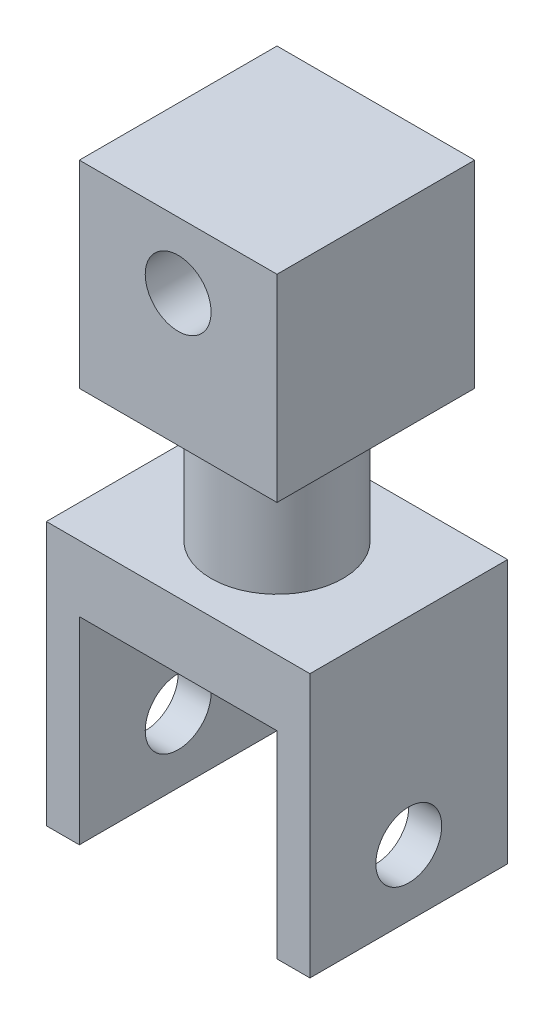
SolidWorks part; units mm, degrees
ref_plane "Front Plane" through (0, 0, 0) normal (0, 0, 1) x (1, 0, 0)
ref_plane "Top Plane" through (0, 0, 0) normal (0, 1, 0) x (1, 0, 0)
ref_plane "Right Plane" through (0, 0, 0) normal (1, 0, 0) x (0, 0, -1)
sketch "Sketch1" plane through (0, 0, 0) normal (0, 1, 0) x (1, 0, 0)
  line L0 (50.8, 76.2) -> (50.8, 0) construction
  line L6 (0, 0) -> (101.6, 0)
  line L7 (0, 0) -> (0, 76.2)
  line L8 (0, 76.2) -> (101.6, 76.2)
  line L9 (101.6, 0) -> (101.6, 76.2)
  line L10 (0, 0) -> (101.6, 76.2) construction
  line L11 (0, 76.2) -> (101.6, 0) construction
  point P7 (50.8, 38.1)
  dimension "D3" = 101.6
  dimension "D4" = 76.2
extrude "Boss-Extrude1" add sketch "Sketch1" along normal blind 101.6
sketch "Sketch3" plane through (0, 0, 0) normal (0, -1, 0) x (1, 0, 0)
  line L0 (101.6, -38.1) -> (0, -38.1) construction
  line L1 (101.6, 0) -> (101.6, -76.2) construction
  line L2 (0, 0) -> (0, -76.2) construction
  line L3 (0, -76.2) -> (101.6, -76.2) construction
  line L4 (88.9, 0) -> (12.7, 0)
  line L5 (88.9, 0) -> (88.9, -76.2)
  line L6 (88.9, -76.2) -> (12.7, -76.2)
  line L7 (12.7, 0) -> (12.7, -76.2)
  line L8 (88.9, 0) -> (12.7, -76.2) construction
  line L9 (88.9, -76.2) -> (12.7, 0) construction
  point P6 (50.8, -38.1)
  dimension "D1" = 76.2
extrude "Cut-Extrude1" cut sketch "Sketch3" against normal blind 76.2
sketch "Sketch4" plane through (0, 101.6, 0) normal (0, 1, 0) x (1, 0, 0)
  line L0 (101.6, 38.1) -> (0, 38.1) construction
  line L1 (101.6, 0) -> (101.6, 76.2) construction
  line L2 (0, 0) -> (0, 76.2) construction
  circle A0 centre (50.8, 38.1) radius 25.4
  dimension "D1" = 50.8
extrude "Boss-Extrude2" add sketch "Sketch4" along normal blind 50.8
sketch "Sketch5" plane through (0, 152.4, 0) normal (0, 1, 0) x (1, 0, 0)
  line L1 (88.9, 76.2) -> (12.7, 76.2)
  line L2 (88.9, 76.2) -> (88.9, 0)
  line L3 (88.9, 0) -> (12.7, 0)
  line L4 (12.7, 76.2) -> (12.7, 0)
  line L5 (88.9, 76.2) -> (12.7, 0) construction
  line L6 (88.9, 0) -> (12.7, 76.2) construction
  point P0 (50.8, 38.1)
  dimension "D1" = 76.2
  dimension "D2" = 76.2
extrude "Boss-Extrude3" add sketch "Sketch5" along normal blind 76.2
sketch "Sketch6" plane through (101.6, 0, 0) normal (1, 0, 0) x (0, 0, -1)
  line L0 (0, 0) -> (76.2, 0) construction
  circle A0 centre (38.1, 25.4) radius 12.7
  dimension "D1" = 25.4
  dimension "D2" = 25.4
extrude "Cut-Extrude2" cut sketch "Sketch6" against normal through all
sketch "Sketch7" plane through (0, 0, -76.2) normal (0, 0, -1) x (-1, 0, 0)
  line L0 (-88.9, 228.6) -> (-12.7, 228.6) construction
  circle A0 centre (-50.8, 203.2) radius 12.7
  dimension "D1" = 25.4
  dimension "D2" = 25.4
extrude "Cut-Extrude3" cut sketch "Sketch7" against normal up to next contours A0
